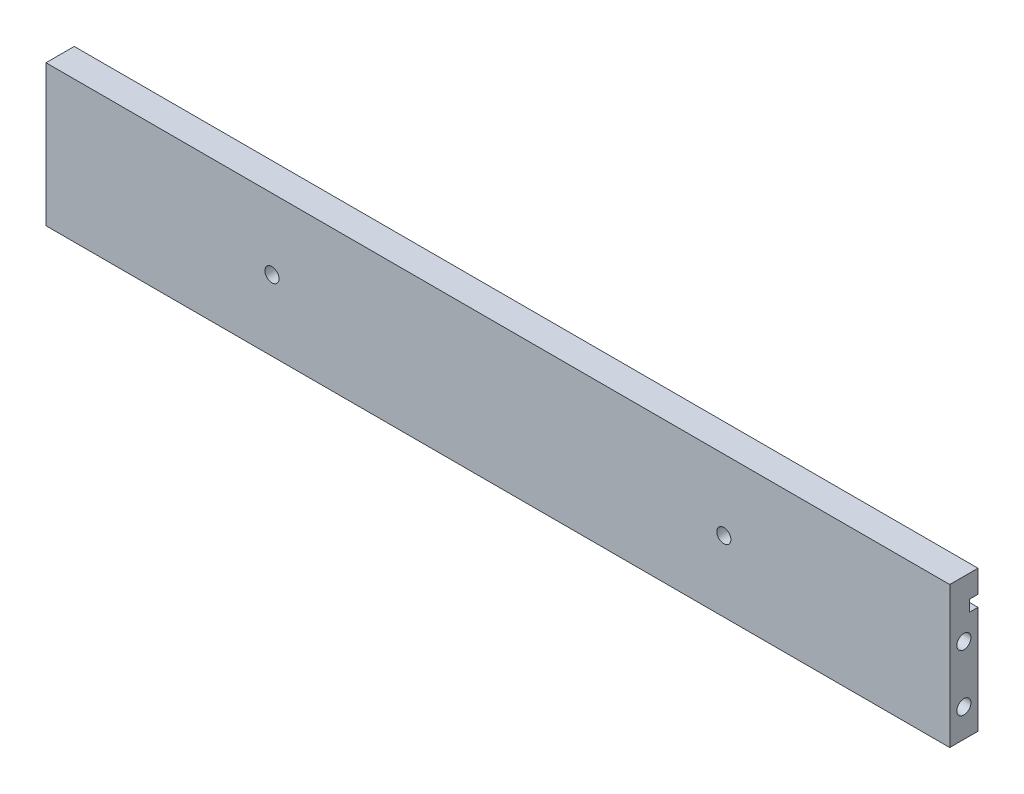
SolidWorks part; units mm, degrees
ref_plane "Ön Düzlem" through (0, 0, 0) normal (0, 0, 1) x (1, 0, 0)
ref_plane "Üst Düzlem" through (0, 0, 0) normal (0, 1, 0) x (1, 0, 0)
ref_plane "Sağ Düzlem" through (0, 0, 0) normal (1, 0, 0) x (0, 0, -1)
sketch "Sketch1" plane through (0, 0, 0) normal (0, 0, 1) x (1, 0, 0)
  line L1 (0, 0) -> (160, 0)
  line L2 (0, 0) -> (0, 25)
  line L3 (0, 25) -> (160, 25)
  line L4 (160, 0) -> (160, 25)
extrude "Boss-Extrude1" add sketch "Sketch1" along normal blind 5
sketch "Sketch2" plane through (0, 0, 0) normal (0, -1, 0) x (1, 0, 0)
  line L0 (0, 5) -> (0, 0) construction
  line L1 (160, 5) -> (160, 0) construction
  line L2 (0, 5) -> (160, 5) construction
  circle A0 centre (40, 2.5) radius 1.25
  circle A1 centre (120, 2.5) radius 1.24
  dimension "D1" = 40
  dimension "D2" = 40
  dimension "D3" = 2.5
  dimension "D4" = 2.5
extrude "Cut-Extrude1" cut sketch "Sketch2" against normal blind 10
cosmetic thread "Cosmetic Thread1" parameters "D2"=3
cosmetic thread "Cosmetic Thread2" parameters "D2"=3
sketch "Sketch5" plane through (0, 0, 0) normal (-1, 0, 0) x (0, 0, 1)
  line L0 (0, 25) -> (0, 0) construction
  line L1 (1.5, 21) -> (0, 21)
  line L2 (1.5, 21) -> (1.5, 19)
  line L3 (1.5, 19) -> (0, 19)
  line L4 (0, 21) -> (0, 19)
  line L5 (5, 25) -> (0, 25) construction
  dimension "D1" = 4
  dimension "D2" = 2
  dimension "D3" = 1.5
extrude "Cut-Extrude4" cut sketch "Sketch5" against normal through all
sketch "Sketch6" plane through (0, 0, 5) normal (0, 0, 1) x (1, 0, 0)
  line L0 (0, 25) -> (0, 0) construction
  line L1 (160, 25) -> (0, 25) construction
  line L2 (160, 0) -> (160, 25) construction
  circle A0 centre (40, 12.5) radius 1.25
  circle A1 centre (120, 12.5) radius 1.25
  dimension "D1" = 40
  dimension "D2" = 12.5
  dimension "D3" = 40
  dimension "D4" = 12.5
extrude "Cut-Extrude5" cut sketch "Sketch6" against normal blind 10
cosmetic thread "Cosmetic Thread3" parameters "D2"=3
cosmetic thread "Cosmetic Thread4" parameters "D2"=3
sketch "Sketch7" plane through (0, 0, 0) normal (-1, 0, 0) x (0, 0, 1)
  line L0 (5, 0) -> (0, 0) construction
  line L1 (5, 25) -> (5, 0) construction
  line L3 (0, 19) -> (0, 0) construction
  circle A0 centre (2.5, 5) radius 1.25
  circle A1 centre (2.5, 15) radius 1.25
  point P10 (-3.7617, 13.4711)
  dimension "D1" = 5
  dimension "D2" = 2.5
  dimension "D3" = 2.5
  dimension "D4" = 10
extrude "Cut-Extrude6" cut sketch "Sketch7" against normal blind 10
cosmetic thread "Cosmetic Thread5" parameters "D2"=3
cosmetic thread "Cosmetic Thread6" parameters "D2"=3
sketch "Sketch8" plane through (160, 0, 0) normal (1, 0, 0) x (0, 0, -1)
  line L1 (-5, 0) -> (-5, 25) construction
  line L2 (0, 0) -> (0, 19) construction
  line L3 (-5, 0) -> (0, 0) construction
  circle A0 centre (-2.5, 5) radius 1.25
  circle A1 centre (-2.5, 15) radius 1.25
  point P6 (0, 0)
  dimension "D1" = 2.5
  dimension "D2" = 2.5
  dimension "D3" = 5
  dimension "D4" = 10
extrude "Cut-Extrude7" cut sketch "Sketch8" against normal blind 10
cosmetic thread "Cosmetic Thread7" parameters "D2"=3
cosmetic thread "Cosmetic Thread8" parameters "D2"=3
